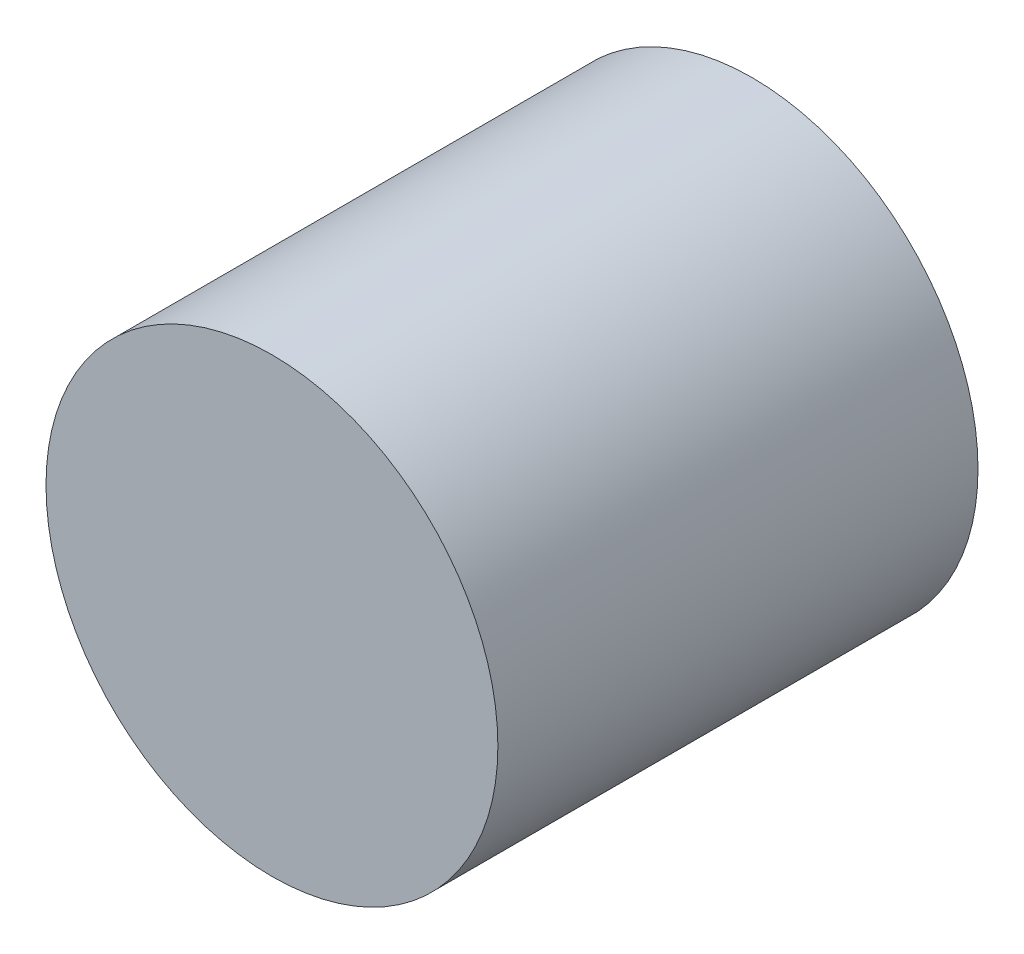
SolidWorks part; units mm, degrees
ref_plane "Front Plane" through (0, 0, 0) normal (0, 0, 1) x (1, 0, 0)
ref_plane "Top Plane" through (0, 0, 0) normal (0, 1, 0) x (1, 0, 0)
ref_plane "Right Plane" through (0, 0, 0) normal (1, 0, 0) x (0, 0, -1)
sketch "Sketch1" plane through (0, 0, 0) normal (0, 0, 1) x (1, 0, 0)
  circle A0 centre (0, 0) radius 4
  dimension "D1" = 8
extrude "Boss-Extrude1" add sketch "Sketch1" along normal blind 8.5
